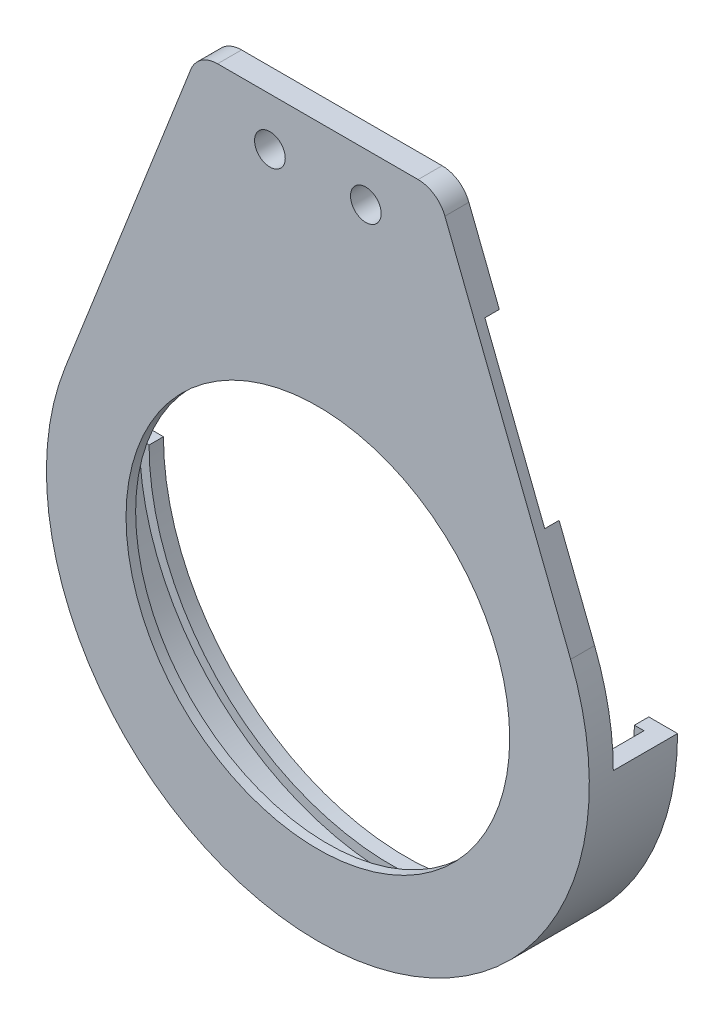
SolidWorks part; units mm, degrees
material "ABS"
ref_plane "前视基准面" through (0, 0, 0) normal (0, 0, 1) x (1, 0, 0)
ref_plane "上视基准面" through (0, 0, 0) normal (0, 1, 0) x (1, 0, 0)
ref_plane "右视基准面" through (0, 0, 0) normal (1, 0, 0) x (0, 0, -1)
other "Configuration Table"
sketch "草图1" plane through (0, 0, 0) normal (0, 0, 1) x (1, 0, 0)
  circle A0 centre (0, 0) radius 21 construction
  circle A1 centre (0, 0) radius 20
  circle A2 centre (0, 0) radius 28.3
  dimension "D1" = 42
  dimension "D2" = 1
  dimension "D3" = 7.3
extrude "凸台-拉伸1" add sketch "草图1" along normal blind 2.5
sketch "草图2" plane through (0, 0, 2.5) normal (0, 0, 1) x (1, 0, 0)
  line L0 (-5, 40.694) -> (5, 40.694) construction
  line L1 (-26.3518, 10.3185) -> (-12.5, 45.694)
  line L2 (26.3518, 10.3185) -> (12.5, 45.694)
  line L3 (-12.5, 45.694) -> (12.5, 45.694)
  line L5 (0, 45.694) -> (0, 0) construction
  circle A2 centre (-5, 40.694) radius 1.6
  circle A3 centre (0, 0) radius 28.3 construction
  arc A4 (-26.3518, 10.3185) -> (26.3518, 10.3185) centre (0, 0) cw
  circle A5 centre (5, 40.694) radius 1.6
  dimension "D2" = 3.2
  dimension "D3" = 25
  dimension "D5" = 10
  dimension "D1" = 5
  dimension "D4" = 41
extrude "凸台-拉伸2" add sketch "草图2" against normal blind 2.5
sketch "草图5" plane through (0, 0, 0) normal (0, 0, -1) x (-1, 0, 0)
  line L0 (-28.3, 0) -> (28.3, 0) construction
  line L1 (-28.3, 0) -> (-26.3, 0)
  line L2 (28.3, 0) -> (26.3, 0)
  arc A0 (-26.3518, 10.3185) -> (26.3518, 10.3185) centre (0, 0) ccw construction
  arc A1 (-28.3, 0) -> (28.3, 0) centre (0, 0) ccw
  arc A2 (-26.3, 0) -> (26.3, 0) centre (0, 0) ccw
  dimension "D1" = 2
extrude "凸台-拉伸3" add sketch "草图5" along normal blind 5.2
sketch "草图6" plane through (0, 0, -5.2) normal (0, 0, -1) x (-1, 0, 0)
  line L0 (-28.3, 0) -> (-25.3, 0)
  line L1 (25.3, 0) -> (28.3, 0)
  arc A0 (-28.3, 0) -> (28.3, 0) centre (0, 0) ccw
  arc A1 (-25.3, 0) -> (25.3, 0) centre (0, 0) ccw
  dimension "D1" = 3
extrude "凸台-拉伸4" add sketch "草图6" along normal blind 1.5
sketch "草图4" plane through (0, 0, 0) normal (0, 0, -1) x (-1, 0, 0)
  line L3 (-22.65, 0) -> (-22.65, 35.694)
  line L4 (-22.65, 35.694) -> (22.65, 35.694)
  line L5 (22.65, 35.694) -> (22.65, 0)
  line L7 (-12.5, 45.694) -> (12.5, 45.694) construction
  arc A0 (-22.65, 0) -> (22.65, 0) centre (0, 0) ccw
  circle A2 centre (-5, 40.694) radius 1.6 construction
  dimension "D1" = 45.3
  dimension "D2" = 5
  dimension "D3" = 5
extrude "切除-拉伸1" cut sketch "草图4" against normal blind 11.5 from offset 10
fillet "圆角1" radius 3 2 edges at (-12.5, 45.694, 1.25) (12.5, 45.694, 1.25)
